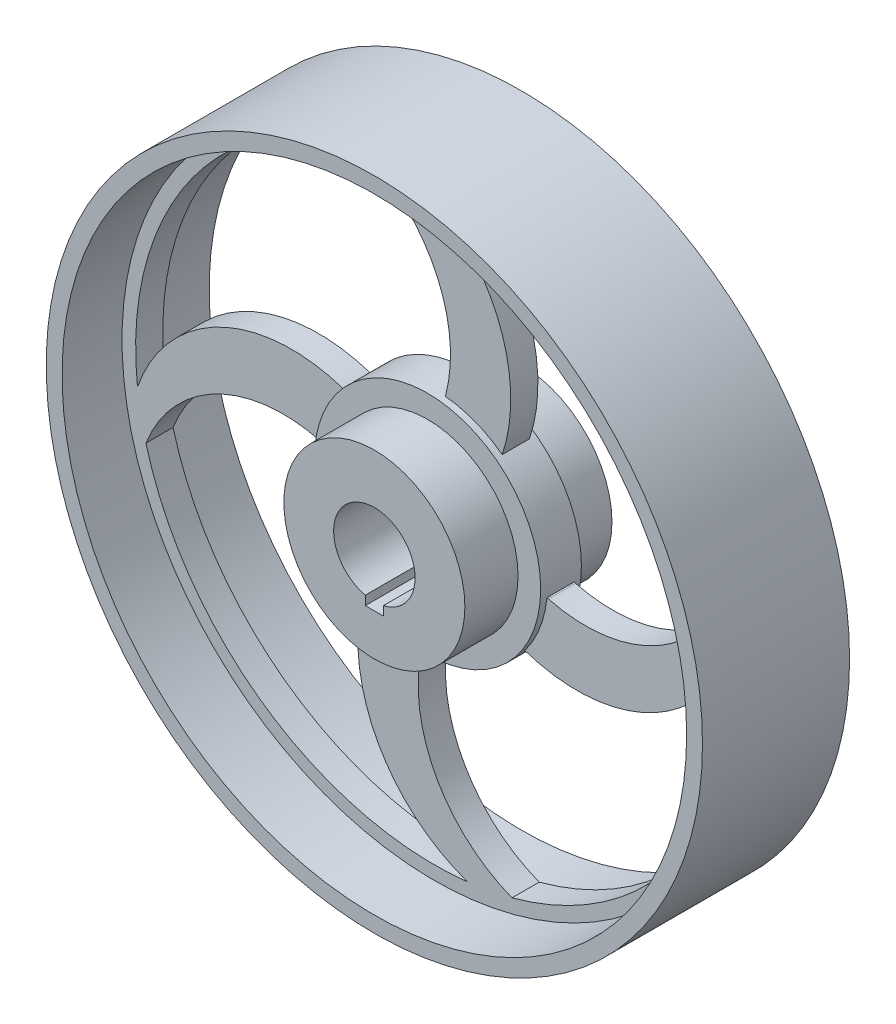
SolidWorks part; units mm, degrees
ref_plane "Front Plane" through (0, 0, 0) normal (0, 0, 1) x (1, 0, 0)
ref_plane "Top Plane" through (0, 0, 0) normal (0, 1, 0) x (1, 0, 0)
ref_plane "Right Plane" through (0, 0, 0) normal (1, 0, 0) x (0, 0, -1)
sketch "Sketch4" plane through (0, 0, 0) normal (0, 0, 1) x (1, 0, 0)
  circle A0 centre (0, 0) radius 1270
extrude "Boss-Extrude2" add sketch "Sketch4" along normal mid plane 457.2
sketch "Sketch5" plane through (0, 0, 0) normal (0, 0, 1) x (1, 0, 0)
  circle A0 centre (0, 0) radius 1016
extrude "Boss-Extrude3" add sketch "Sketch5" along normal mid plane 1651
sketch "Sketch6" plane through (0, 0, 0) normal (0, 0, 1) x (1, 0, 0)
  line L1 (101.6, -547.3682) -> (-101.6, -547.3682)
  line L2 (101.6, -547.3682) -> (101.6, -445.7682)
  line L3 (-101.6, -547.3682) -> (-101.6, -445.7682)
  arc A0 (101.6, -445.7682) -> (-101.6, -445.7682) centre (0, 0) ccw
  dimension "D1" = 203.2
  dimension "D3" = 914.4
  dimension "D2" = 101.6
extrude "Cut-Extrude2" cut sketch "Sketch6" against normal mid plane 1651 contours A0 L3 L1 L2
sketch "Sketch7" plane through (0, 0, 0) normal (0, 0, 1) x (1, 0, 0)
  circle A0 centre (0, 0) radius 3505.2
  circle A1 centre (0, 0) radius 3352.8
extrude "Boss-Extrude5" add sketch "Sketch7" along normal mid plane 304.8 separate body
sketch "Sketch9" plane through (0, 0, 0) normal (0, 0, 1) x (1, 0, 0)
  circle A0 centre (0, 0) radius 3505.2
  circle A1 centre (0, 0) radius 3683
extrude "Boss-Extrude8" add sketch "Sketch9" along normal mid plane 1651
sketch "Sketch10" plane through (0, 0, 0) normal (0, 0, 1) x (1, 0, 0)
  line L2 (128.3237, 1280.531) -> (124.019, 1263.9301)
  line L3 (1280.531, -128.3237) -> (1263.9301, -124.019)
  line L4 (-128.3237, -1280.531) -> (-124.019, -1263.9301)
  line L5 (-1280.531, 128.3237) -> (-1263.9301, 124.019)
  circle A3 centre (0, 0) radius 3352.8 construction
  arc A7 (-872.1692, 3237.3737) -> (128.3237, 1280.531) centre (-1473.3013, 1695.8404) cw
  arc A8 (-373.0565, 3331.9809) -> (762, 1016) centre (-974.1887, 1601.2328) cw
  circle A9 centre (0, 0) radius 1270 construction
  arc A10 (3237.3737, 872.1692) -> (1280.531, -128.3237) centre (1695.8404, 1473.3013) cw
  arc A11 (3331.9809, 373.0565) -> (1016, -762) centre (1601.2328, 974.1887) cw
  arc A12 (872.1692, -3237.3737) -> (-128.3237, -1280.531) centre (1473.3013, -1695.8404) cw
  arc A13 (373.0565, -3331.9809) -> (-762, -1016) centre (974.1887, -1601.2328) cw
  arc A14 (-3237.3737, -872.1692) -> (-1280.531, 128.3237) centre (-1695.8404, -1473.3013) cw
  arc A15 (-3331.9809, -373.0565) -> (-1016, 762) centre (-1601.2328, -974.1887) cw
  arc A16 (-762, -1016) -> (-124.019, -1263.9301) centre (0, 0) ccw
  arc A17 (-3331.9809, -373.0565) -> (-3237.3737, -872.1692) centre (0, 0) ccw
  arc A18 (-373.0565, 3331.9809) -> (-872.1692, 3237.3737) centre (0, 0) ccw
  arc A19 (3331.9809, 373.0565) -> (3237.3737, 872.1692) centre (0, 0) ccw
  arc A20 (373.0565, -3331.9809) -> (872.1692, -3237.3737) centre (0, 0) ccw
  arc A21 (1016, -762) -> (1263.9301, -124.019) centre (0, 0) ccw
  arc A22 (762, 1016) -> (124.019, 1263.9301) centre (0, 0) ccw
  arc A23 (-1016, 762) -> (-1263.9301, 124.019) centre (0, 0) ccw
  point P0 (0, 0)
  point P40 (0, 0)
  dimension "D1" = 508
  dimension "D2" = 508
  dimension "D3" = 4
extrude "Boss-Extrude10" add sketch "Sketch10" along normal mid plane 304.8
